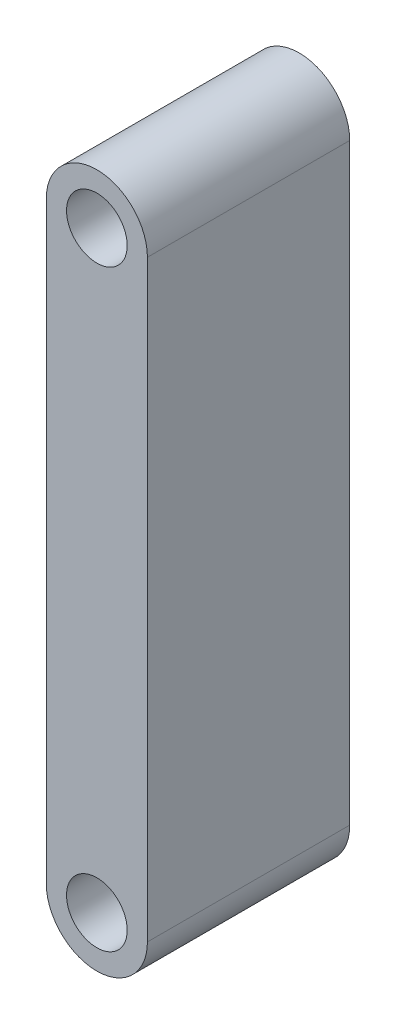
SolidWorks part; units mm, degrees
ref_plane "Piano frontale" through (0, 0, 0) normal (0, 0, 1) x (1, 0, 0)
ref_plane "Piano superiore" through (0, 0, 0) normal (0, 1, 0) x (1, 0, 0)
ref_plane "Piano destro" through (0, 0, 0) normal (1, 0, 0) x (0, 0, -1)
sketch "Schizzo2" plane through (0, 0, 0) normal (0, 0, 1) x (1, 0, 0)
  line L0 (0, 253.4564) -> (0, -39.6436) construction
  line L1 (25, 253.4564) -> (25, -39.6436)
  line L2 (-25, 253.4564) -> (-25, -39.6436)
  arc A0 (25, 253.4564) -> (-25, 253.4564) centre (0, 253.4564) ccw
  arc A1 (-25, -39.6436) -> (25, -39.6436) centre (0, -39.6436) ccw
  circle A2 centre (0, 253.4564) radius 15
  circle A3 centre (0, -39.6436) radius 15
  point P3 (0, 106.9064)
  dimension "D2" = 30
  dimension "D3" = 30
  dimension "D1" = 293.1
  dimension "D4" = 50
extrude "Estrusione-Estrusione1" add sketch "Schizzo2" along normal mid plane 100
